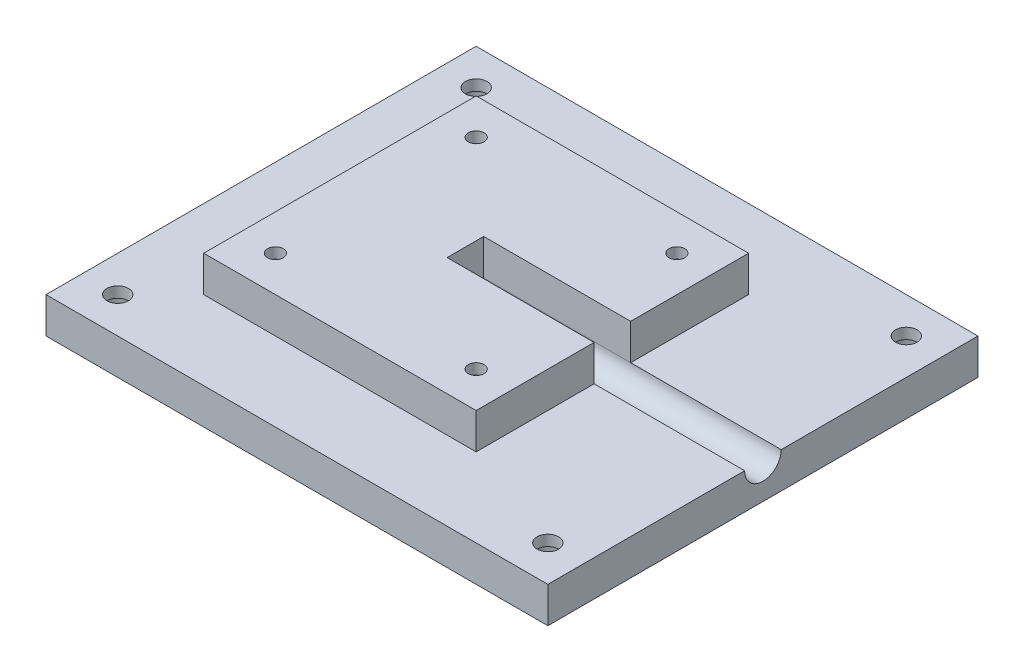
SolidWorks part; units mm, degrees
ref_plane "前视基准面" through (0, 0, 0) normal (0, 0, 1) x (1, 0, 0)
ref_plane "上视基准面" through (0, 0, 0) normal (0, 1, 0) x (1, 0, 0)
ref_plane "右视基准面" through (0, 0, 0) normal (1, 0, 0) x (0, 0, -1)
sketch "草图1" plane through (0, 0, 0) normal (0, 1, 0) x (1, 0, 0)
  line L1 (-35, 30) -> (35, 30)
  line L2 (-35, 30) -> (-35, -30)
  line L3 (-35, -30) -> (35, -30)
  line L4 (35, 30) -> (35, -30)
  line L5 (-35, 30) -> (35, -30) construction
  line L6 (-35, -30) -> (35, 30) construction
  point P0 (0, 0)
  dimension "D1" = 70
  dimension "D2" = 60
extrude "凸台-拉伸1" add sketch "草图1" along normal blind 5
sketch "草图2" plane through (0, 5, 0) normal (0, 1, 0) x (1, 0, 0)
  line L0 (35, -30) -> (35, 30) construction
  line L1 (-24, 19) -> (14, 19)
  line L2 (-24, 19) -> (-24, -19)
  line L3 (-24, -19) -> (14, -19)
  line L4 (14, 19) -> (14, -19)
  line L5 (35, 30) -> (-35, 30) construction
  line L6 (-35, -30) -> (35, -30) construction
  line L7 (-35, 30) -> (-35, -30) construction
  dimension "D1" = 21
  dimension "D2" = 11
  dimension "D3" = 11
  dimension "D4" = 11
extrude "凸台-拉伸2" add sketch "草图2" along normal blind 5
sketch "草图3" plane through (0, 10, 0) normal (0, 1, 0) x (1, 0, 0)
  line L0 (14, 19) -> (-24, 19) construction
  line L1 (-24, 19) -> (-24, -19) construction
  line L2 (-5, 19) -> (-5, -19) construction
  line L3 (-24, -19) -> (14, -19) construction
  line L4 (-24, 0) -> (14, 0) construction
  line L5 (14, -19) -> (14, 19) construction
  circle A0 centre (-19, 14) radius 1.1
  circle A1 centre (9, 14) radius 1.1
  circle A2 centre (-19, -14) radius 1.1
  circle A3 centre (9, -14) radius 1.1
  dimension "D1" = 2.2
  dimension "D2" = 5
  dimension "D3" = 5
extrude "切除-拉伸1" cut sketch "草图3" against normal up to next
sketch "草图4" plane through (0, 0, 0) normal (0, -1, 0) x (1, 0, 0)
  circle A0 centre (-19, -14) radius 3
  circle A1 centre (-19, 14) radius 3
  circle A2 centre (9, 14) radius 3
  circle A3 centre (9, -14) radius 3
  point P5 (-19, 14)
  point P9 (9, 14)
  point P13 (9, -14)
  dimension "D1" = 6
  dimension "D2" = 6
  dimension "D3" = 6
  dimension "D4" = 6
extrude "切除-拉伸2" cut sketch "草图4" against normal offset from surface (8.5 mm away) 1.5 up to face at (9, 10, -15.1)
sketch "草图5" plane through (0, 5, 0) normal (0, 1, 0) x (1, 0, 0)
  line L0 (35, 30) -> (-35, 30) construction
  line L1 (-35, 30) -> (-35, -30) construction
  line L2 (0, 30) -> (0, -30) construction
  line L3 (-35, -30) -> (35, -30) construction
  line L4 (-35, 0) -> (35, 0) construction
  line L5 (35, -30) -> (35, 30) construction
  circle A0 centre (-30, 25) radius 1.5
  circle A1 centre (30, 25) radius 1.5
  circle A2 centre (30, -25) radius 1.5
  circle A3 centre (-30, -25) radius 1.5
  dimension "D1" = 3
  dimension "D2" = 5
  dimension "D3" = 5
extrude "切除-拉伸3" cut sketch "草图5" against normal up to next
sketch "草图6" plane through (0, 0, 0) normal (0, -1, 0) x (1, 0, 0)
  line L0 (-35, 0) -> (35, 0) construction
  line L1 (-35, -30) -> (-35, 30) construction
  line L2 (35, 30) -> (35, -30) construction
  line L3 (0, -30) -> (0, 30) construction
  line L4 (35, -30) -> (-35, -30) construction
  line L5 (-35, 30) -> (35, 30) construction
  circle A0 centre (-30, -25) radius 3
  circle A1 centre (30, -25) radius 3
  circle A2 centre (30, 25) radius 3
  circle A3 centre (-30, 25) radius 3
  dimension "D1" = 6
extrude "切除-拉伸4" cut sketch "草图6" against normal offset from surface (3.5 mm away) 1.5 up to face at (30, 5, -26.5)
sketch "草图7" plane through (35, 0, 0) normal (1, 0, 0) x (0, 0, -1)
  line L0 (-30, 5) -> (30, 5) construction
  line L1 (-19, 10) -> (19, 10) construction
  line L3 (2.55, 5) -> (2.55, 10)
  line L4 (2.55, 10) -> (-2.55, 10)
  line L5 (-2.55, 5) -> (-2.55, 10)
  arc A0 (-2.55, 5) -> (2.55, 5) centre (0, 5) ccw
  dimension "D1" = 5.1
  dimension "D2" = 5
extrude "切除-拉伸5" cut sketch "草图7" against normal blind 41.5
